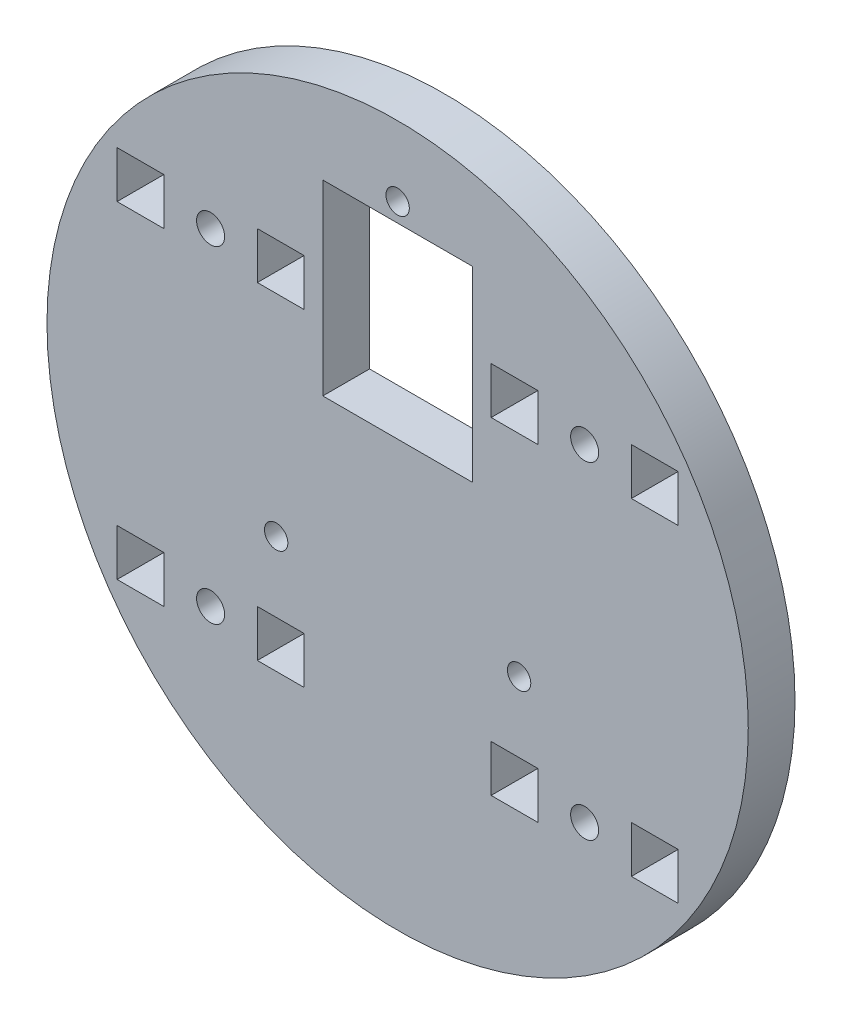
SolidWorks part; units mm, degrees
ref_plane "Front Plane" through (0, 0, 0) normal (0, 0, 1) x (1, 0, 0)
ref_plane "Top Plane" through (0, 0, 0) normal (0, 1, 0) x (1, 0, 0)
ref_plane "Right Plane" through (0, 0, 0) normal (1, 0, 0) x (0, 0, -1)
sketch "Sketch1" plane through (0, 0, 0) normal (0, 0, 1) x (1, 0, 0)
  line L0 (0, 0) -> (0, -37.5) construction
  line L1 (0, 0) -> (32.476, 18.75) construction
  line L2 (0, 0) -> (-32.476, 18.75) construction
  circle A0 centre (0, 0) radius 32.5 construction
  circle A1 centre (0, 0) radius 37.5
  arc A3 (-25.9343, -27.0862) -> (25.9343, -27.0862) centre (0, 0) cw construction
  dimension "D1" = 5
  dimension "D4" = 75
  dimension "D2" = 120
  dimension "D3" = 120
extrude "Boss-Extrude1" add sketch "Sketch1" along normal blind 5
sketch "Sketch9" plane through (0, 0, 5) normal (0, 0, 1) x (1, 0, 0)
  line L0 (0, 0) -> (0, -37.5) construction
  line L1 (-40, 0) -> (40, 0) construction
  line L2 (0, 0) -> (0, 40) construction
  line L3 (0, 0) -> (34.641, -20) construction
  line L17 (0, 0) -> (-34.641, -20) construction
  line L19 (0, -37.5) -> (0, 0) construction
  line L30 (-8, 8) -> (8, 8)
  line L31 (-8, 8) -> (-8, 28)
  line L32 (-8, 28) -> (8, 28)
  line L33 (8, 8) -> (8, 28)
  circle A1 centre (0, 0) radius 37 construction
  circle A2 centre (0, 0) radius 40 construction
  circle A8 centre (0, 15) radius 1.25 construction
  circle A9 centre (0, 30) radius 1.25
  circle A11 centre (0, 0) radius 37.5 construction
  circle A12 centre (25.9808, -15) radius 1.25 construction
  circle A13 centre (12.9904, -7.5) radius 1.25
  circle A14 centre (-25.9808, -15) radius 1.25 construction
  circle A15 centre (-12.9904, -7.5) radius 1.25
  point P8 (0, 0)
  point P25 (0, 0)
  point P26 (0, 0)
  point P28 (0, 0)
  point P46 (0, 0)
  line B0 (15, 17.5) -> (25, 17.5) construction
  line B1 (15, 20) -> (10, 20)
  line B2 (15, 20) -> (15, 15)
  line B3 (15, 15) -> (10, 15)
  line B4 (10, 20) -> (10, 15)
  line B5 (25, 20) -> (30, 20)
  line B6 (25, 20) -> (25, 15)
  line B7 (25, 15) -> (30, 15)
  line B8 (30, 20) -> (30, 15)
  line B9 (20, 17.5) -> (20, 24.4724) construction
  circle B10 centre (20, 17.5) radius 1.5
  line B11 (-25, 20) -> (-30, 20)
  line B12 (-25, 20) -> (-25, 15)
  line B13 (-25, 15) -> (-30, 15)
  line B14 (-30, 20) -> (-30, 15)
  line B15 (-15, 20) -> (-10, 20)
  line B16 (-15, 20) -> (-15, 15)
  line B17 (-15, 15) -> (-10, 15)
  line B18 (-10, 20) -> (-10, 15)
  line B19 (-20, 17.5) -> (-20, 24.4724) construction
  circle B20 centre (-20, 17.5) radius 1.5
  line B21 (15, -17.5) -> (25, -17.5) construction
  line B22 (15, -20) -> (10, -20)
  line B23 (15, -20) -> (15, -15)
  line B24 (15, -15) -> (10, -15)
  line B25 (10, -20) -> (10, -15)
  line B26 (25, -20) -> (30, -20)
  line B27 (25, -20) -> (25, -15)
  line B28 (25, -15) -> (30, -15)
  line B29 (30, -20) -> (30, -15)
  circle B30 centre (20, -17.5) radius 1.5
  line B31 (-25, -20) -> (-30, -20)
  line B32 (-25, -20) -> (-25, -15)
  line B33 (-25, -15) -> (-30, -15)
  line B34 (-30, -20) -> (-30, -15)
  line B35 (-15, -20) -> (-10, -20)
  line B36 (-15, -20) -> (-15, -15)
  line B37 (-15, -15) -> (-10, -15)
  line B38 (-10, -20) -> (-10, -15)
  circle B39 centre (-20, -17.5) radius 1.5
  dimension "D6" = 80
  dimension "D7" = 74
  dimension "D10" = 2.5
  dimension "D2" = 35
  dimension "D3" = 8
  dimension "D4" = 40
  dimension "D5" = 3
  dimension "D8" = 15
  dimension "D9" = 15
  dimension "D11" = 3
  dimension "D12" = 20
  dimension "D15" = 16
sketch_block_instance "Trou M3 plots 5mm-34"
sketch_block "Trou M3 plots 5mm" parameters "D2"=3, "D1"=5, "D3"=5, "D4"=10
sketch_block_instance "Trou M3 plots 5mm-35"
sketch_block_instance "Trou M3 plots 5mm-36"
sketch_block_instance "Trou M3 plots 5mm-37"
sketch_block_instance "Trou M3 plots 5mm-55"
sketch_block_instance "Trou M3 plots 5mm-56"
sketch_block_instance "Trou M3 plots 5mm-72"
sketch_block_instance "Trou M3 plots 5mm-80"
sketch_block_instance "Trou M3 plots 5mm-81"
extrude "Cut-Extrude5" cut sketch "Sketch9" against normal through all
